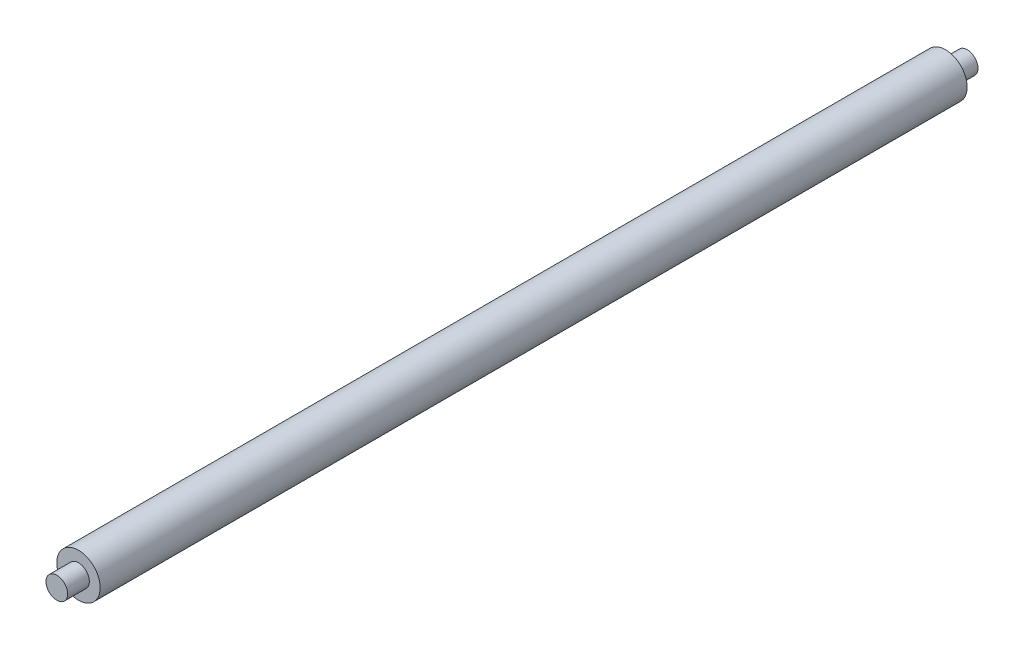
SolidWorks part; units mm, degrees
material "Plain Carbon Steel"
ref_plane "Front Plane" through (0, 0, 0) normal (0, 0, 1) x (1, 0, 0)
ref_plane "Top Plane" through (0, 0, 0) normal (0, 1, 0) x (1, 0, 0)
ref_plane "Right Plane" through (0, 0, 0) normal (1, 0, 0) x (0, 0, -1)
sketch "Sketch1" plane through (0, 0, 0) normal (0, 0, 1) x (1, 0, 0)
  circle A0 centre (0, 0) radius 5
  dimension "D1" = 10
extrude "Boss-Extrude1" add sketch "Sketch1" along normal mid plane 200
sketch "Sketch2" plane through (0, 0, 100) normal (0, 0, 1) x (1, 0, 0)
  circle A0 centre (0, 0) radius 2.5
  dimension "D1" = 5
extrude "Boss-Extrude2" add sketch "Sketch2" along normal blind 5
mirror "Mirror1" about plane through (0, 0, 0) normal (0, 0, 1) of "Boss-Extrude2"
